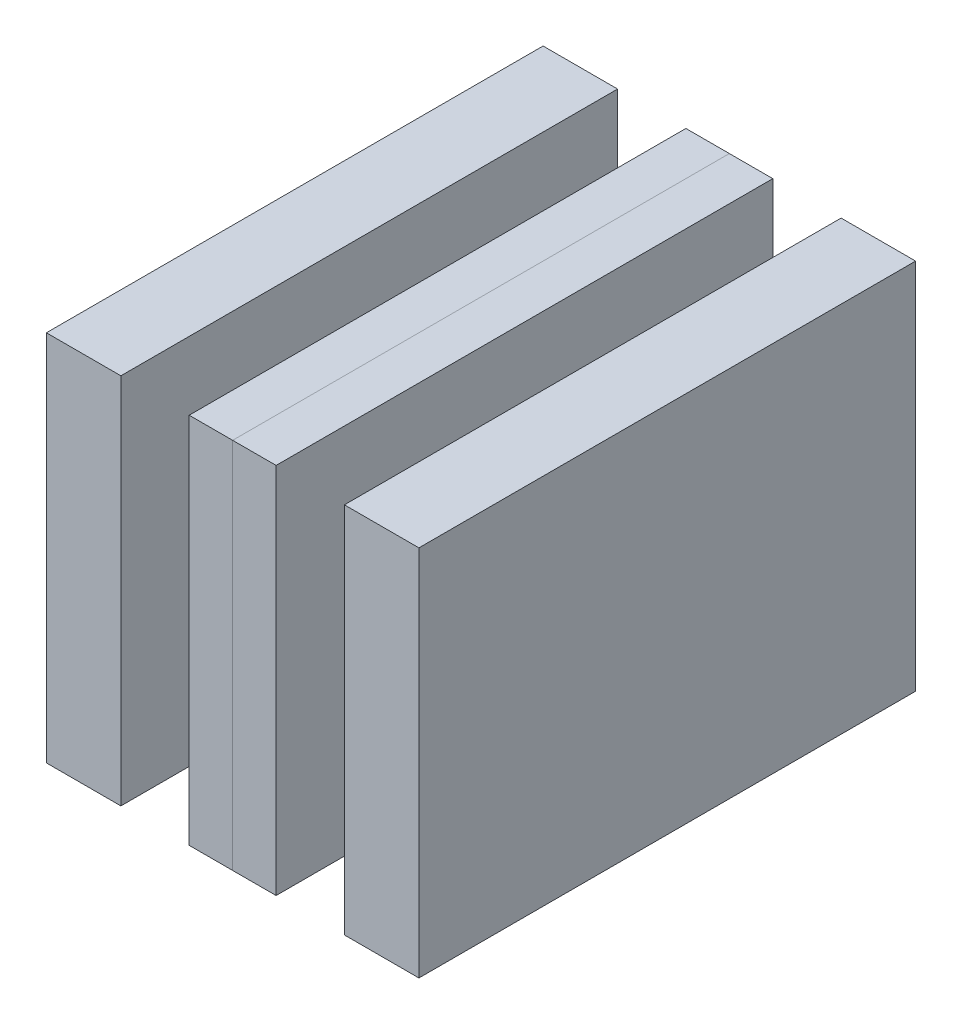
SolidWorks part; units mm, degrees
ref_plane "Front Plane" through (0, 0, 0) normal (0, 0, 1) x (1, 0, 0)
ref_plane "Top Plane" through (0, 0, 0) normal (0, 1, 0) x (1, 0, 0)
ref_plane "Right Plane" through (0, 0, 0) normal (1, 0, 0) x (0, 0, -1)
sketch "Sketch1" plane through (0, 0, 0) normal (0, 0, 1) x (1, 0, 0)
  line L1 (0, 0) -> (3, 0)
  line L2 (0, 0) -> (0, 15)
  line L3 (0, 15) -> (3, 15)
  line L4 (3, 0) -> (3, 15)
  line L5 (5.75, 15) -> (7.5, 15)
  line L6 (5.75, 15) -> (5.75, 0)
  line L7 (5.75, 0) -> (7.5, 0)
  line L8 (7.5, 15) -> (7.5, 0)
  dimension "D1" = 15
  dimension "D2" = 1.75
  dimension "D3" = 4.5
  dimension "D4" = 7.5
extrude "Boss-Extrude1" add sketch "Sketch1" along normal blind 20
mirror "Mirror1" about plane through (7.5, 15, 20) normal (-1, 0, 0) of bodies 102 101
